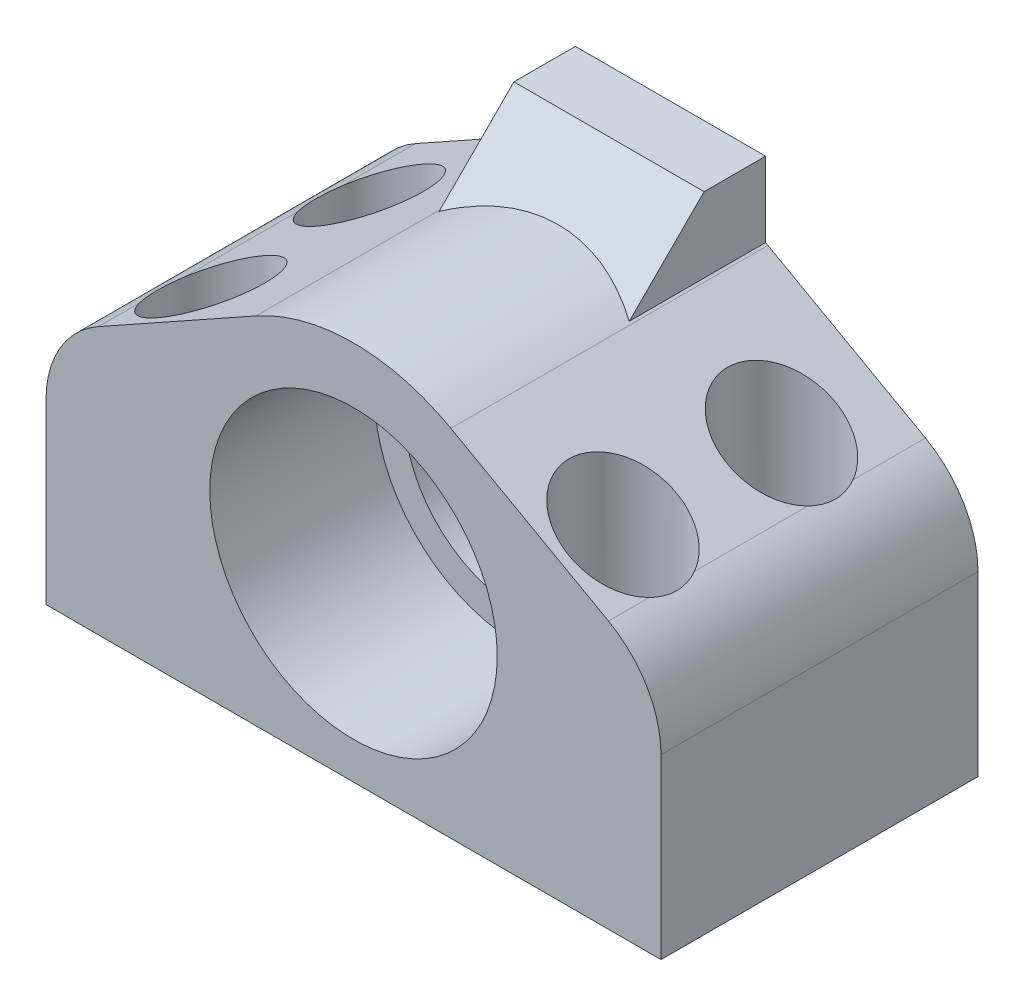
SolidWorks part; units mm, degrees
material "ABS"
ref_plane "Front Plane" through (0, 0, 0) normal (0, 0, 1) x (1, 0, 0)
ref_plane "Top Plane" through (0, 0, 0) normal (0, 1, 0) x (1, 0, 0)
ref_plane "Right Plane" through (0, 0, 0) normal (1, 0, 0) x (0, 0, -1)
sketch "Sketch1" plane through (0, 0, 0) normal (0, 0, 1) x (1, 0, 0)
  line L0 (0, 0) -> (0, 33.2505) construction
  line L2 (24.25, 4) -> (24.25, -10)
  line L3 (24.25, -10) -> (-24.25, -10)
  line L4 (-24.25, 4) -> (-24.25, -10)
  line L7 (-20.11, 11.0556) -> (-7.6823, 17.9994)
  line L8 (20.11, 11.0556) -> (7.6823, 17.9994)
  arc A0 (7.6823, 17.9994) -> (-7.6823, 17.9994) centre (0, 4.25) ccw
  arc A1 (20.11, 11.0556) -> (24.25, 4) centre (16.1678, 4) cw
  arc A2 (-20.11, 11.0556) -> (-24.25, 4) centre (-16.1678, 4) ccw
  circle A3 centre (0, 4.25) radius 9
  point P0 (0, 0)
  dimension "D2" = 31.5
  dimension "D3" = 30
  dimension "D4" = 14
  dimension "D9" = 18
  dimension "D1" = 48.5
  dimension "D5" = 4.14
  dimension "D6" = 4.14
  dimension "D7" = 14
  dimension "D8" = 10
extrude "Boss-Extrude1" add sketch "Sketch1" along normal blind 25
sketch "Sketch2" plane through (0, 0, 25) normal (0, 0, 1) x (1, 0, 0)
  circle A0 centre (0, 4.25) radius 11.335
  dimension "D1" = 22.67
extrude "Cut-Extrude1" cut sketch "Sketch2" against normal blind 13
sketch "Sketch3" plane through (0, 0, 0) normal (0, 0, -1) x (-1, 0, 0)
  circle A0 centre (0, 4.25) radius 11.335
  dimension "D1" = 22.67
extrude "Cut-Extrude2" cut sketch "Sketch3" against normal blind 7
sketch "Sketch4" plane through (0, 0, 0) normal (0, 0, -1) x (-1, 0, 0)
  line L0 (-7.5, 18.1012) -> (-7.5, 24)
  line L1 (-20.11, 11.0556) -> (-7.6823, 17.9994) construction
  line L2 (-7.5, 24) -> (7.5, 24)
  line L3 (7.5, 24) -> (7.5, 18.1012)
  line L4 (7.6823, 17.9994) -> (20.11, 11.0556) construction
  line L5 (24.25, -10) -> (-24.25, -10) construction
  arc A1 (7.5, 18.1012) -> (-7.5, 18.1012) centre (0, 4.25) ccw
  dimension "D1" = 34
  dimension "D3" = 7.5
extrude "Boss-Extrude2" add sketch "Sketch4" against normal blind 4.85 separate body
sketch "Sketch5" plane through (7.5, 0, 0) normal (1, 0, 0) x (0, 0, -1)
  line L0 (-4.85, 24) -> (-4.85, 18.1012)
  line L1 (-4.85, 18.1012) -> (-10.7488, 18.1012)
  line L2 (-10.7488, 18.1012) -> (-4.85, 24)
  dimension "D1" = 45
extrude "Boss-Extrude3" add sketch "Sketch5" against normal blind 15
sketch "Sketch6" plane through (0, -10, 0) normal (0, -1, 0) x (1, 0, 0)
  line L0 (0, 0) -> (0, 13.75) construction
  line L1 (16.25, 7.5) -> (-16.25, 7.5) construction
  line L2 (16.25, 7.5) -> (16.25, 20) construction
  line L3 (16.25, 20) -> (-16.25, 20) construction
  line L4 (-16.25, 7.5) -> (-16.25, 20) construction
  line L5 (16.25, 7.5) -> (-16.25, 20) construction
  line L6 (16.25, 20) -> (-16.25, 7.5) construction
  line L7 (-24.25, 25) -> (24.25, 25) construction
  circle A0 centre (-16.25, 20) radius 2.25
  circle A1 centre (16.25, 20) radius 2.25
  circle A2 centre (16.25, 7.5) radius 2.25
  circle A3 centre (-16.25, 7.5) radius 2.25
  point P0 (0, 13.75)
  dimension "D4" = 4.5
  dimension "D5" = 4.5
  dimension "D6" = 4.5
  dimension "D7" = 4.5
  dimension "D1" = 12.5
  dimension "D2" = 32.5
  dimension "D3" = 5
extrude "Cut-Extrude3" cut sketch "Sketch6" against normal through all
ref_plane "Plane1" through (0, 0, 0) normal (0, -1, 0) x (-1, 0, 0)
sketch "Sketch7" plane through (0, 0, 0) normal (0, -1, 0) x (-1, 0, 0)
  circle A0 centre (16.25, -20) radius 4.25
  circle A1 centre (16.25, -7.5) radius 4.25
  circle A2 centre (-16.25, -7.5) radius 4.25
  circle A3 centre (-16.25, -20) radius 4.25
  dimension "D1" = 8.5
  dimension "D2" = 8.5
  dimension "D3" = 8.5
  dimension "D4" = 8.5
extrude "Cut-Extrude4" cut sketch "Sketch7" against normal through all
